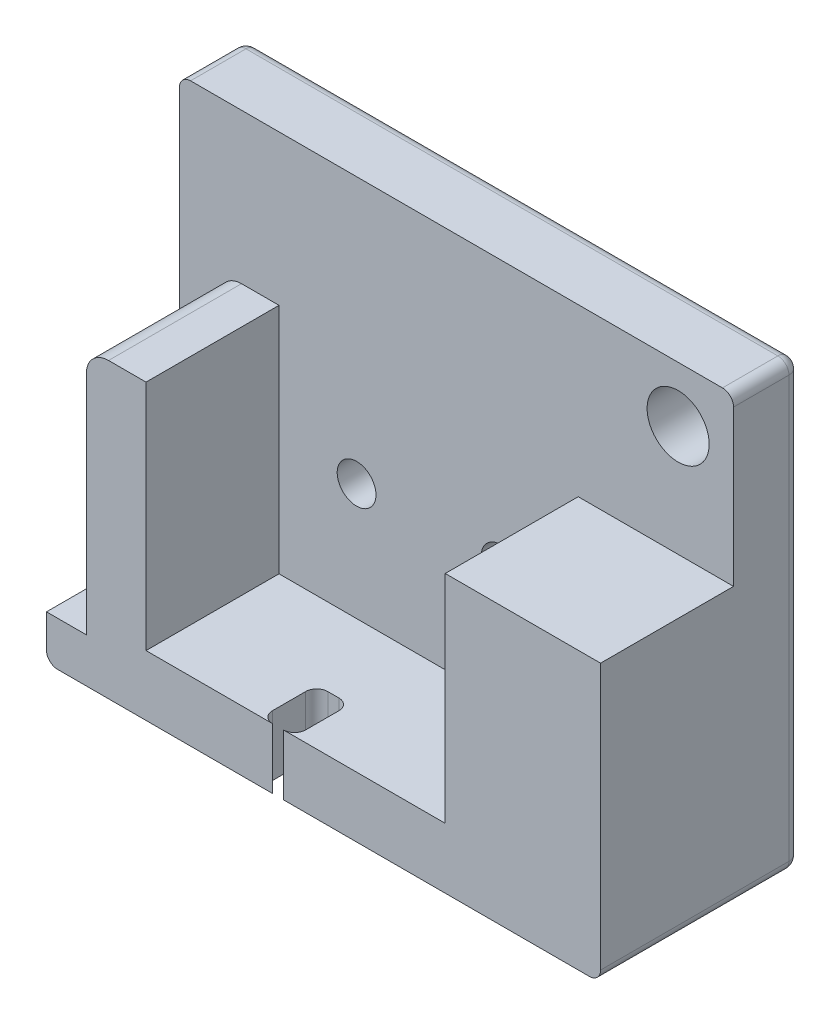
SolidWorks part; units mm, degrees
ref_plane "Plan de face" through (0, 0, 0) normal (0, 0, 1) x (1, 0, 0)
ref_plane "Plan de dessus" through (0, 0, 0) normal (0, 1, 0) x (1, 0, 0)
ref_plane "Plan de droite" through (0, 0, 0) normal (1, 0, 0) x (0, 0, -1)
sketch "Esquisse1" plane through (0, 0, 0) normal (0, 0, 1) x (1, 0, 0)
  line L1 (0, 0) -> (25, 0)
  line L2 (0, 0) -> (0, 20)
  line L3 (0, 20) -> (25, 20)
  line L4 (25, 0) -> (25, 20)
  circle A0 centre (22.5, 17.5) radius 1.4
  circle A1 centre (14.4914, 8) radius 0.875
  circle A2 centre (7.9914, 8) radius 0.875
  dimension "D3" = 1.75
  dimension "D7" = 2.8
  dimension "D8" = 8
  dimension "D1" = 25
  dimension "D2" = 20
  dimension "D4" = 6.5
  dimension "D5" = 2.5
  dimension "D6" = 2.5
extrude "Boss.-Extru.1" add sketch "Esquisse1" along normal blind 3
sketch "Esquisse2" plane through (0, 0, 3) normal (0, 0, 1) x (1, 0, 0)
  line L0 (0, 2) -> (1.8, 2)
  line L1 (0, 20) -> (0, 0) construction
  line L2 (1.8, 2) -> (1.8, 12.2223)
  line L3 (2.8, 13.2223) -> (4.4914, 13.2223)
  line L4 (4.4914, 13.2223) -> (4.4914, 2.7307)
  line L5 (4.4914, 2.7307) -> (17.9914, 2.7307)
  line L6 (17.9914, 2.7307) -> (17.9914, 12.4938)
  line L7 (17.9914, 12.4938) -> (25, 12.4938)
  line L8 (25, 0) -> (25, 20) construction
  line L9 (25, 12.4938) -> (25, 0)
  line L10 (25, 0) -> (0, 0)
  line L11 (0, 0) -> (0, 2)
  circle A0 centre (7.9914, 8) radius 0.875 construction
  circle A1 centre (14.4914, 8) radius 0.875 construction
  arc A2 (1.8, 12.2223) -> (2.8, 13.2223) centre (2.8, 12.2223) cw
  dimension "D3" = 3.5
  dimension "D5" = 1
  dimension "D1" = 1.8
  dimension "D2" = 3.5
  dimension "D4" = 2
extrude "Boss.-Extru.2" add sketch "Esquisse2" along normal blind 6
sketch "Esquisse3" plane through (0, 2.7307, 0) normal (0, 1, 0) x (1, 0, 0)
  line L0 (9.6925, -8.5) -> (9.6925, -7)
  line L1 (17.9914, -9) -> (4.4914, -9) construction
  line L2 (10.1925, -6.5) -> (10.6925, -6.5)
  line L3 (11.1925, -7) -> (11.1925, -8.5)
  line L4 (10.1925, -9) -> (10.6925, -9)
  arc A0 (9.6925, -8.5) -> (10.1925, -9) centre (10.1925, -8.5) ccw
  arc A1 (11.1925, -8.5) -> (10.6925, -9) centre (10.6925, -8.5) cw
  arc A2 (10.6925, -6.5) -> (11.1925, -7) centre (10.6925, -7) cw
  arc A3 (10.1925, -6.5) -> (9.6925, -7) centre (10.1925, -7) ccw
  point P8 (9.6925, -9)
  point P11 (11.1925, -9)
  dimension "D3" = 0.5
  dimension "D1" = 1.5
  dimension "D2" = 2.5
extrude "Enlèv. mat.-Extru.1" cut sketch "Esquisse3" against normal blind 6
sketch "Esquisse4" plane through (1.8, 0, 0) normal (-1, 0, 0) x (0, 0, 1)
  line L0 (9, 12.2223) -> (9, 2) construction
  line L1 (9, 0) -> (0, 0) construction
  circle A0 centre (6, 8) radius 2
  dimension "D1" = 4
  dimension "D2" = 3
  dimension "D3" = 8
extrude "Enlèv. mat.-Extru.2" cut sketch "Esquisse4" against normal blind 1
fillet "Congé1" radius 0.5 8 edges at (12.5, 0, 0) (25, 10, 0) (12.5, 20, 0) (0, 10, 0) (25, 20, 1.5) (0, 20, 1.5) (0, 0, 4.5) (25, 0, 4.5)
sketch "Esquisse5" plane through (0, 0, 0) normal (0, -1, 0) x (1, 0, 0)
  circle A1 centre (21.1231, 5.5985) radius 1.4
  dimension "D2" = 2.8
extrude "Enlèv. mat.-Extru.3" cut sketch "Esquisse5" against normal blind 6
